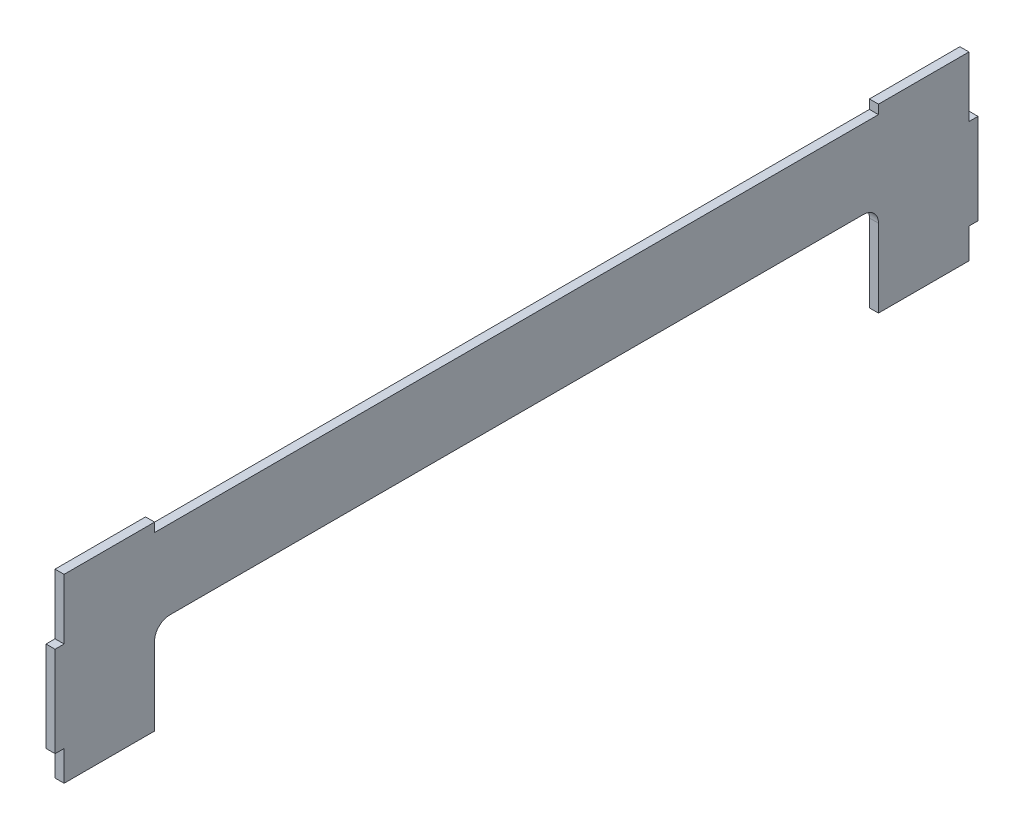
SolidWorks part; units mm, degrees
ref_plane "Front Plane" through (0, 0, 0) normal (0, 0, 1) x (1, 0, 0)
ref_plane "Top Plane" through (0, 0, 0) normal (0, 1, 0) x (1, 0, 0)
ref_plane "Right Plane" through (0, 0, 0) normal (1, 0, 0) x (0, 0, -1)
sketch "Sketch1" plane through (0, 0, 0) normal (1, 0, 0) x (0, 0, -1)
  line L0 (-169.0909, 50) -> (-139.0909, 50)
  line L1 (-139.0909, 50) -> (-139.0909, 47)
  line L2 (-139.0909, 47) -> (100.9091, 47)
  line L3 (100.9091, 47) -> (100.9091, 50)
  line L4 (100.9091, 50) -> (130.9091, 50)
  line L5 (130.9091, 50) -> (130.9091, 30)
  line L6 (130.9091, 30) -> (133.9091, 30)
  line L7 (133.9091, 30) -> (133.9091, 0)
  line L8 (133.9091, 0) -> (130.9091, 0)
  line L9 (130.9091, 0) -> (130.9091, -10)
  line L10 (130.9091, -10) -> (-169.0909, -10)
  line L11 (-169.0909, -10) -> (-169.0909, 0)
  line L12 (-169.0909, 0) -> (-172.0909, 0)
  line L13 (-172.0909, 0) -> (-172.0909, 30)
  line L14 (-172.0909, 30) -> (-169.0909, 30)
  line L15 (-169.0909, 30) -> (-169.0909, 50)
  dimension "D1" = 300
  dimension "D2" = 240
  dimension "D3" = 30
  dimension "D4" = 30
  dimension "D5" = 30
  dimension "D6" = 30
  dimension "D7" = 20
  dimension "D8" = 10
  dimension "D9" = 10
  dimension "D10" = 20
  dimension "D11" = 3
  dimension "D12" = 3
  dimension "D13" = 3
  dimension "D14" = 3
extrude "Boss-Extrude1" add sketch "Sketch1" along normal blind 3
sketch "Sketch2" plane through (0, 0, 0) normal (-1, 0, 0) x (0, 0, 1)
  line L0 (-100.9091, -10) -> (-100.9091, 15.819)
  line L1 (169.0909, -10) -> (-130.9091, -10) construction
  line L2 (-95.9091, 20.819) -> (134.0909, 20.819)
  line L3 (139.0909, 15.819) -> (139.0909, -10)
  line L4 (-130.9091, -10) -> (-130.9091, 0) construction
  arc A0 (139.0909, 15.819) -> (134.0909, 20.819) centre (134.0909, 15.819) ccw
  arc A1 (-100.9091, 15.819) -> (-95.9091, 20.819) centre (-95.9091, 15.819) cw
  point P11 (139.0909, 20.819)
  point P14 (-100.9091, 20.819)
  dimension "D3" = 5
  dimension "D1" = 240
  dimension "D2" = 30
extrude "Cut-Extrude2" cut sketch "Sketch2" against normal blind 3 and the other way through all flip side to cut
